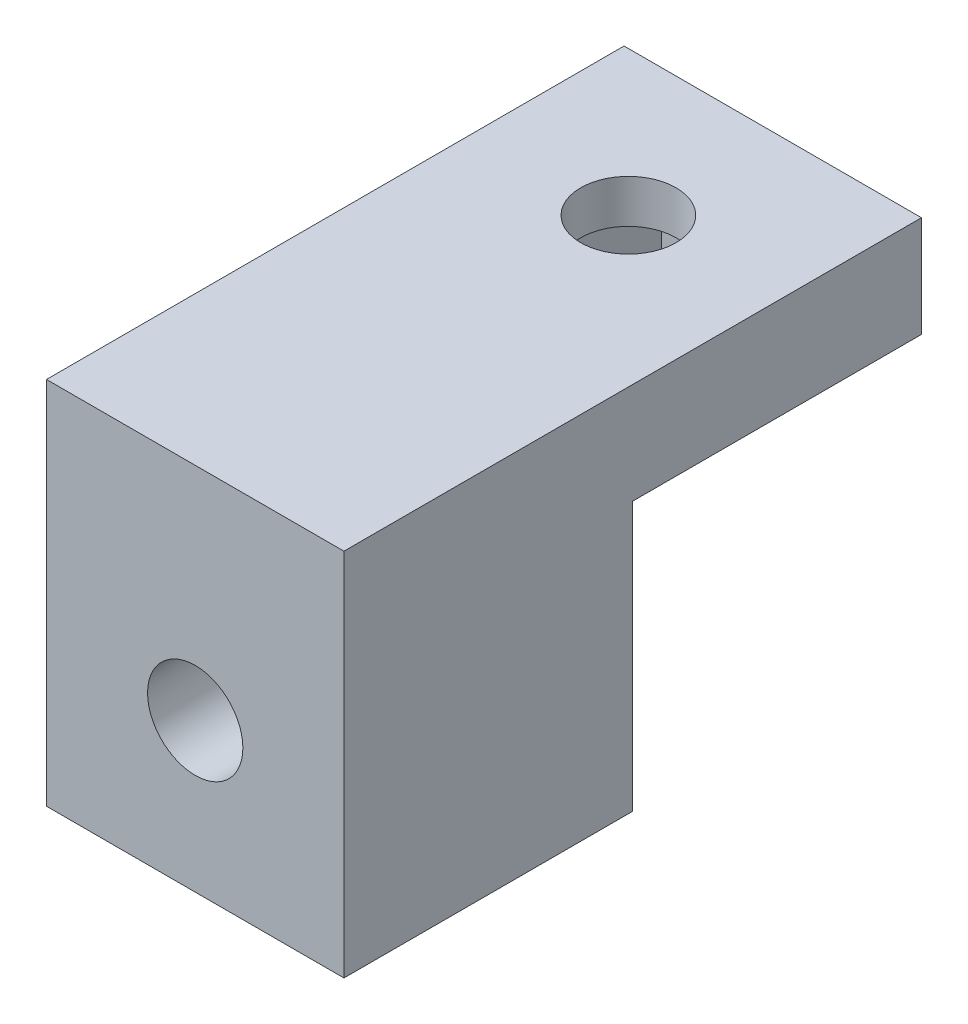
SolidWorks part; units mm, degrees
ref_plane "Alzado" through (0, 0, 0) normal (0, 0, 1) x (1, 0, 0)
ref_plane "Planta" through (0, 0, 0) normal (0, 1, 0) x (1, 0, 0)
ref_plane "Vista lateral" through (0, 0, 0) normal (1, 0, 0) x (0, 0, -1)
sketch "Sketch1" plane through (0, 0, 0) normal (0, 0, 1) x (1, 0, 0)
  line L0 (-5.15, 7.65) -> (5.15, 7.65)
  line L1 (-5.15, 7.65) -> (-5.15, -5.15)
  line L2 (-5.15, -5.15) -> (5.15, -5.15)
  line L4 (5.15, 7.65) -> (5.15, -5.15)
  circle A0 centre (0, 0) radius 1.65
  point P0 (0, 0)
  point P10 (-1.65, 0)
  point P11 (0, -1.65)
  point P12 (0, 1.65)
  dimension "D1" = 3.3
  dimension "D2" = 3.5
  dimension "D3" = 3.5
  dimension "D4" = 6
  dimension "D5" = 3.5
extrude "Boss-Extrude2" add sketch "Sketch1" along normal mid plane 10
sketch "Sketch2" plane through (0, 0, -5) normal (0, 0, -1) x (-1, 0, 0)
  line L2 (-1.65, -2.8) -> (1.65, -2.8)
  line L3 (-1.65, 2.8) -> (1.65, 2.8)
  line L4 (3.3964, 0) -> (1.65, -2.8)
  line L5 (-3.3964, 0) -> (-1.65, -2.8)
  line L6 (3.3964, 0) -> (1.65, 2.8)
  line L7 (-1.65, 2.8) -> (-3.3964, 0)
  circle A0 centre (0, 0) radius 1.65
  point P3 (0, -2.8)
  point P11 (0, 2.8)
  dimension "D8" = 3.3
  dimension "D1" = 3.3
  dimension "D2" = 3.3
  dimension "D3" = 3.3
  dimension "D4" = 3.3
  dimension "D5" = 3.3
  dimension "D6" = 3.3
  dimension "D7" = 5.6
extrude "Cut-Extrude1" cut sketch "Sketch2" against normal blind 2 contours A0 | L2 L4 L6 L3 L7 L5
sketch "Sketch3" plane through (0, 0, -5) normal (0, 0, -1) x (-1, 0, 0)
  line L0 (-5.15, 4.15) -> (5.15, 4.15)
  line L4 (-5.15, 7.65) -> (-5.15, -5.15)
  line L5 (-5.15, -5.15) -> (5.15, -5.15)
  line L6 (5.15, -5.15) -> (5.15, 7.65)
  line L7 (5.15, 7.65) -> (-5.15, 7.65)
  line L8 (-5.15, 7.65) -> (-5.15, 4.15)
  line L10 (5.15, 4.15) -> (5.15, 7.65)
  line L11 (5.15, 7.65) -> (-5.15, 7.65)
  dimension "D2" = 3.5
  dimension "D1" = 0
extrude "Boss-Extrude3" add sketch "Sketch3" along normal blind 10
sketch "Sketch4" plane through (0, 4.15, 0) normal (0, -1, 0) x (1, 0, 0)
  line L0 (-5.15, -10) -> (5.15, -10) construction
  line L3 (-1.65, -12.8) -> (1.65, -12.8)
  line L4 (-1.65, -7.2) -> (1.65, -7.2)
  line L5 (3.3964, -10) -> (1.65, -12.8)
  line L6 (5.15, -5) -> (-5.15, -5)
  line L9 (-5.15, -5) -> (-5.15, -15)
  line L10 (-5.15, -15) -> (5.15, -15)
  line L11 (5.15, -15) -> (5.15, -5)
  line L12 (5.15, -5) -> (-5.15, -5)
  line L15 (-5.15, -5) -> (-5.15, -15)
  line L16 (-5.15, -15) -> (5.15, -15)
  line L17 (5.15, -15) -> (5.15, -5)
  line L18 (-3.3964, -10) -> (-1.65, -12.8)
  line L19 (3.3964, -10) -> (1.65, -7.2)
  line L20 (-1.65, -7.2) -> (-3.3964, -10)
  circle A1 centre (0, -10) radius 1.65
  point P10 (0, -10)
  point P14 (0, -12.8)
  point P22 (0, -7.2)
  dimension "D2" = 3.3
  dimension "D3" = 3.3
  dimension "D4" = 3.3
  dimension "D5" = 3.3
  dimension "D6" = 3.3
  dimension "D7" = 3.3
  dimension "D8" = 3.3
  dimension "D9" = 5.6
  dimension "D1" = 0
extrude "Cut-Extrude2" cut sketch "Sketch4" against normal blind 2 contours L0 L18 L3 L5 A1 | L20 L0 A1 L19 L4 | A1 L0 | L0 A1
sketch "Sketch5" plane through (0, 6.15, 0) normal (0, -1, 0) x (1, 0, 0)
  line L0 (-5.15, -15) -> (-5.15, -5) construction
  circle A0 centre (0, -10) radius 1.65
  point P6 (-5.15, -10)
  dimension "D1" = 3.3
extrude "Cut-Extrude3" cut sketch "Sketch5" against normal up to surface (1.5 mm away) up to face at (0, 7.65, -5)
